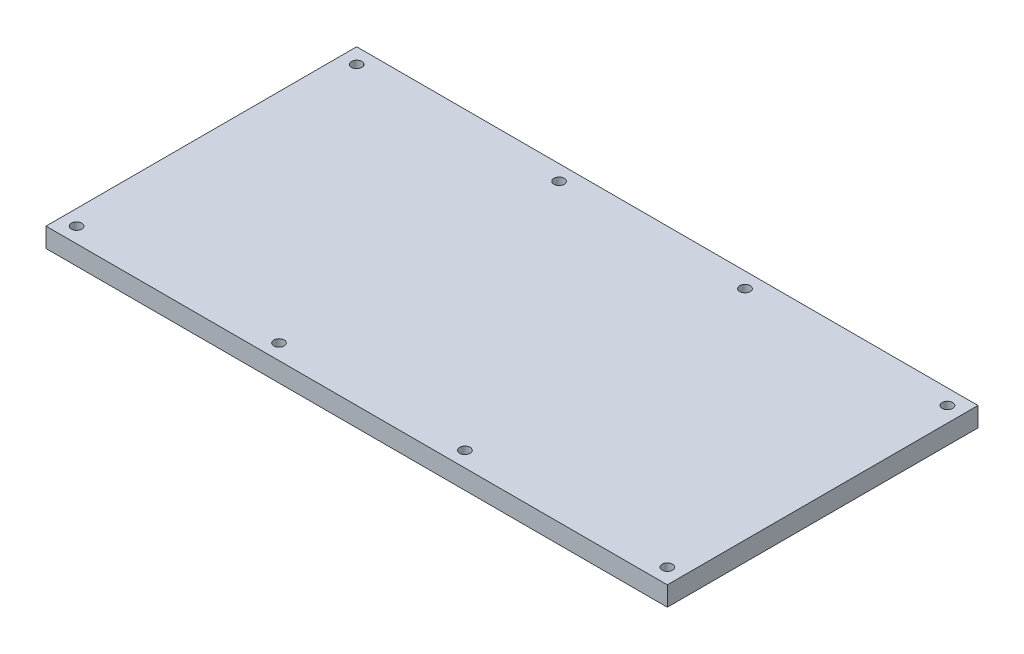
SolidWorks part; units mm, degrees
ref_plane "Front Plane" through (0, 0, 0) normal (0, 0, 1) x (1, 0, 0)
ref_plane "Top Plane" through (0, 0, 0) normal (0, 1, 0) x (1, 0, 0)
ref_plane "Right Plane" through (0, 0, 0) normal (1, 0, 0) x (0, 0, -1)
sketch "Sketch1" plane through (0, 0, 0) normal (0, 1, 0) x (1, 0, 0)
  line L1 (0, 0) -> (76.2, 0)
  line L2 (0, 0) -> (0, 101.6)
  line L3 (0, 101.6) -> (76.2, 101.6)
  line L4 (76.2, 0) -> (76.2, 101.6)
  dimension "D1" = 101.6
  dimension "D2" = 76.2
extrude "Boss-Extrude1" add sketch "Sketch1" along normal blind 6.35
sketch "Sketch2" plane through (0, 6.35, 0) normal (0, 1, 0) x (1, 0, 0)
  line L0 (38.1, 0) -> (38.1, 68.5972) construction
  line L1 (76.2, 0) -> (76.2, 101.6) construction
  line L2 (0, 50.8) -> (66.4895, 50.8) construction
  line L3 (0, 0) -> (76.2, 0) construction
  line L6 (0, 101.6) -> (0, 0) construction
  line L7 (76.2, 101.6) -> (0, 101.6) construction
  circle A0 centre (5, 96.6) radius 1.7
  circle A1 centre (71.2, 96.6) radius 1.7
  circle A2 centre (71.2, 5) radius 1.7
  circle A3 centre (5, 5) radius 1.7
  point P2 (33.2447, 50.8)
  point P3 (38.1, 34.2986)
  point P20 (76.2, 50.8)
  point P23 (38.1, 0)
  dimension "D1" = 3.4
  dimension "D2" = 5
  dimension "D3" = 5
extrude "Cut-Extrude1" cut sketch "Sketch2" against normal through all
ref_plane "Plane1" through (-25.4, 0, 0) normal (-1, 0, 0) x (0, 0, 1)
mirror "Mirror2" about plane through (-25.4, 0, 0) normal (-1, 0, 0) of bodies 102
sketch "Sketch3" plane through (-50.8, 0, 0) normal (1, 0, 0) x (0, 0, -1)
  line L0 (0, 6.35) -> (101.6, 6.35)
  line L1 (101.6, 6.35) -> (101.6, 0)
  line L2 (101.6, 0) -> (0, 0)
  line L3 (0, 0) -> (0, 6.35)
extrude "Boss-Extrude2" add sketch "Sketch3" along normal up to surface (50.8 mm away) up to face at (0, 3.175, -50.8)
